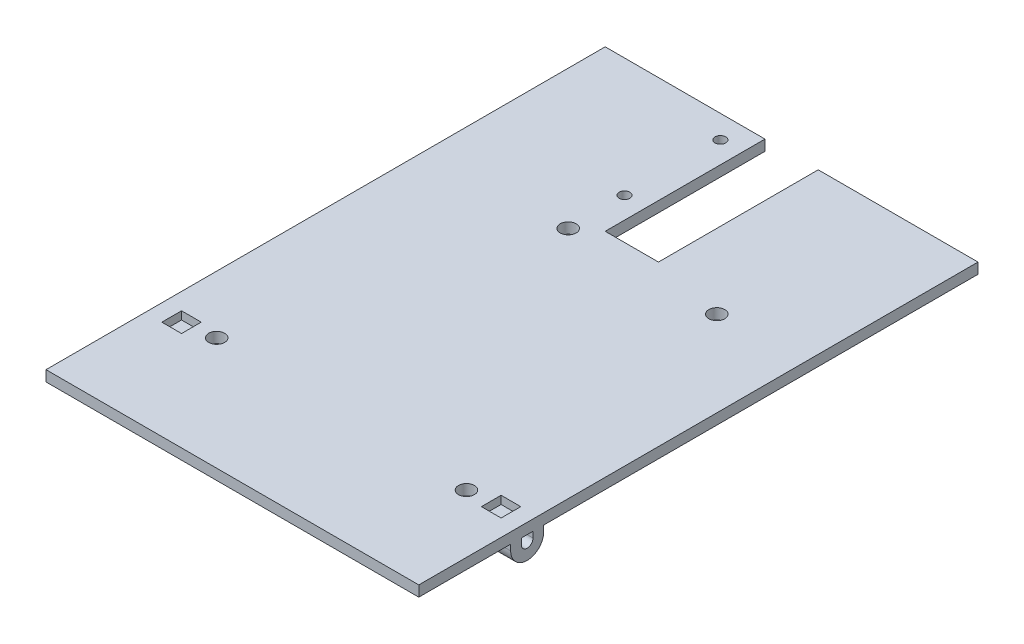
SolidWorks part; units mm, degrees
ref_plane "Front Plane" through (0, 0, 0) normal (0, 0, 1) x (1, 0, 0)
ref_plane "Top Plane" through (0, 0, 0) normal (0, 1, 0) x (1, 0, 0)
ref_plane "Right Plane" through (0, 0, 0) normal (1, 0, 0) x (0, 0, -1)
sketch "Sketch1" plane through (0, 0, 0) normal (0, 1, 0) x (1, 0, 0)
  line L0 (-5, 52.5) -> (-5, 22.5)
  line L1 (35, 52.5) -> (5, 52.5)
  line L2 (35, 52.5) -> (35, -52.5)
  line L3 (35, -52.5) -> (-35, -52.5)
  line L4 (-35, 52.5) -> (-35, -52.5)
  line L5 (35, 52.5) -> (-35, -52.5) construction
  line L6 (35, -52.5) -> (-35, 52.5) construction
  line L7 (-5, 22.5) -> (5, 22.5)
  line L8 (5, 22.5) -> (5, 52.5)
  line L9 (5, 52.5) -> (-5, 52.5) construction
  line L10 (-5, 52.5) -> (-35, 52.5)
  line L11 (-34.3, -15) -> (-35, -15) construction
  line L13 (-34.3, 11.75) -> (-34.3, -41.75) construction
  line L14 (-34.3, -41.75) -> (34.3, -41.75) construction
  line L15 (34.3, 11.75) -> (34.3, -41.75) construction
  line L18 (34.3, -15) -> (35, -15) construction
  line L19 (0, 0) -> (0, 33.4823) construction
  line L20 (-31.55, -30.5) -> (-28.45, -30.5)
  line L21 (-31.55, -30.5) -> (-31.55, -33.6)
  line L22 (-31.55, -33.6) -> (-28.45, -33.6)
  line L23 (-28.45, -30.5) -> (-28.45, -33.6)
  line L24 (-31.55, -30.5) -> (-28.45, -33.6) construction
  line L25 (-31.55, -33.6) -> (-28.45, -30.5) construction
  line L26 (31.55, -33.6) -> (28.45, -33.6)
  line L27 (28.45, -30.5) -> (28.45, -33.6)
  line L28 (31.55, -30.5) -> (28.45, -30.5)
  line L29 (31.55, -30.5) -> (31.55, -33.6)
  circle A8 centre (-9.0499, 48.1783) radius 1
  circle A9 centre (-9.0499, 30.1783) radius 1
  point P0 (0, 0)
  point P9 (0, 22.5)
  point P11 (-9.0499, 48.1783)
  point P36 (-15, -15)
  point P39 (-30, -32.05)
  point P43 (30, -32.05)
  point P45 (30, -30.5)
  point P46 (28.45, -32.05)
  dimension "D3" = 75
  dimension "D17" = 2
  dimension "D18" = 18
  dimension "D2" = 70
  dimension "D11" = 30
  dimension "D12" = 10
  dimension "D14" = 68.6
  dimension "D19" = 3.1
  dimension "D20" = 60
  dimension "D21" = 53
extrude "Boss-Extrude1" add sketch "Sketch1" along normal blind 2
sketch "Sketch3" plane through (35, 0, 0) normal (1, 0, 0) x (0, 0, -1)
  line L0 (-35.25, 0) -> (-35.25, -1.1)
  line L1 (52.5, 0) -> (-52.5, 0) construction
  line L2 (-29.05, -1.1) -> (-29.05, 0)
  line L3 (-29.05, 0) -> (-35.25, 0)
  line L4 (-52.5, 2) -> (-52.5, 0) construction
  line L5 (-33.25, -1.1) -> (-33.25, 0)
  line L6 (-31.05, -1.1) -> (-31.05, 0)
  arc A0 (-35.25, -1.1) -> (-29.05, -1.1) centre (-32.15, -1.1) ccw
  arc A1 (-33.25, -1.1) -> (-31.05, -1.1) centre (-32.15, -1.1) ccw
  circle A2 centre (-32.15, -1.1) radius 20.35 construction
  arc A3 (-32.15, 0) -> (-33.25, -1.1) centre (-32.15, -1.1) ccw construction
  arc A4 (-31.05, -1.1) -> (-32.15, 0) centre (-32.15, -1.1) ccw construction
  point P10 (-52.5, -1.1)
  line M7 (-52.5, 0) -> (52.5, 0)
  dimension "D1" = 2.2
  dimension "D2" = 2
  dimension "D3" = 40.7
extrude "Boss-Extrude2" add sketch "Sketch3" against normal blind 3 contours A1 L5 L0 A0 L2 L6 M7
ref_plane "Plane1" through (0, 0, 0) normal (1, 0, 0) x (0, 0, -1)
mirror "Mirror1" about plane through (0, 0, 0) normal (1, 0, 0) of "Boss-Extrude2"
sketch "Sketch4" plane through (0, 0, 0) normal (0, -1, 0) x (1, 0, 0)
  line L1 (-31.55, 33.6) -> (-28.45, 33.6)
  line L2 (-31.55, 33.6) -> (-31.55, 30.5)
  line L3 (-31.55, 30.5) -> (-28.45, 30.5)
  line L4 (-28.45, 33.6) -> (-28.45, 30.5)
  line L5 (-31.55, 33.6) -> (-28.45, 30.5) construction
  line L6 (-31.55, 30.5) -> (-28.45, 33.6) construction
  line L7 (28.45, 33.6) -> (31.55, 33.6)
  line L8 (28.45, 33.6) -> (28.45, 30.5)
  line L9 (28.45, 30.5) -> (31.55, 30.5)
  line L10 (31.55, 33.6) -> (31.55, 30.5)
  line L11 (28.45, 33.6) -> (31.55, 30.5) construction
  line L12 (28.45, 30.5) -> (31.55, 33.6) construction
  point P4 (-30, 32.05)
  point P11 (30, 32.05)
extrude "Boss-Extrude3" add sketch "Sketch4" against normal blind 0.5
sketch "Sketch5" plane through (0, 2, 0) normal (0, 1, 0) x (1, 0, 0)
  line L0 (28.45, -30.5) -> (28.45, -33.6) construction
  line L1 (28.45, -33.6) -> (31.55, -33.6) construction
  line L2 (31.55, -33.6) -> (31.55, -30.5) construction
  line L3 (31.55, -30.5) -> (28.45, -30.5) construction
  line L4 (-31.55, -30.5) -> (-31.55, -33.6) construction
  line L5 (-31.55, -33.6) -> (-28.45, -33.6) construction
  line L6 (-28.45, -33.6) -> (-28.45, -30.5) construction
  line L7 (-28.45, -30.5) -> (-31.55, -30.5) construction
  line L8 (28.45, -30.5) -> (28.45, -33.6) construction
  line L9 (28.45, -33.6) -> (31.55, -33.6) construction
  line L10 (31.55, -33.6) -> (31.55, -30.5) construction
  line L11 (31.55, -30.5) -> (28.45, -30.5) construction
  line L12 (-31.55, -30.5) -> (-31.55, -33.6) construction
  line L13 (-31.55, -33.6) -> (-28.45, -33.6) construction
  line L14 (-28.45, -33.6) -> (-28.45, -30.5) construction
  line L15 (-28.45, -30.5) -> (-31.55, -30.5) construction
  line L16 (-31.85, -33.9) -> (-28.15, -33.9)
  line L17 (-28.15, -33.9) -> (-28.15, -30.2)
  line L18 (-28.15, -30.2) -> (-31.85, -30.2)
  line L19 (-31.85, -30.2) -> (-31.85, -33.9)
  line L20 (28.15, -33.9) -> (31.85, -33.9)
  line L21 (31.85, -33.9) -> (31.85, -30.2)
  line L22 (31.85, -30.2) -> (28.15, -30.2)
  line L23 (28.15, -30.2) -> (28.15, -33.9)
  dimension "D1" = 0.3
extrude "Cut-Extrude1" cut sketch "Sketch5" against normal up to surface (1.5 mm away) up to face at (-30, 0.5, 32.05)
sketch "Sketch6" plane through (0, 2, 0) normal (0, 1, 0) x (1, 0, 0)
  line L0 (-28.15, -33.9) -> (-28.15, -30.2) construction
  line L1 (28.15, -30.2) -> (28.15, -33.9) construction
  line L2 (-5, 22.5) -> (5, 22.5) construction
  line L3 (35, -52.5) -> (-35, -52.5) construction
  circle A0 centre (-8.95, 19.5) radius 1.5
  circle A1 centre (18.95, 19.5) radius 1.5
  circle A2 centre (24.05, -32.6) radius 1.5
  circle A3 centre (-24.15, -31.3) radius 1.5
  point P8 (-26.5487, -24.964)
  point P9 (0, 0)
  point P10 (-9.0596, 3.9301)
  point P11 (-8.6663, 13.6257)
  point P16 (-8.95, 5.3687)
  point P17 (-8.95, 8.0286)
  point P18 (-8.95, 10.6732)
  point P19 (-8.95, 11.0601)
  point P20 (-8.95, 10.3065)
  dimension "D1" = 3
  dimension "D2" = 50.8
  dimension "D3" = 27.9
  dimension "D4" = 15.2
  dimension "D5" = 5.1
  dimension "D6" = 1.3
  dimension "D7" = 4
  dimension "D8" = 4.1
  dimension "D9" = 3
  dimension "D10" = 21.2
extrude "Cut-Extrude2" cut sketch "Sketch6" against normal through all both and the other way through all
